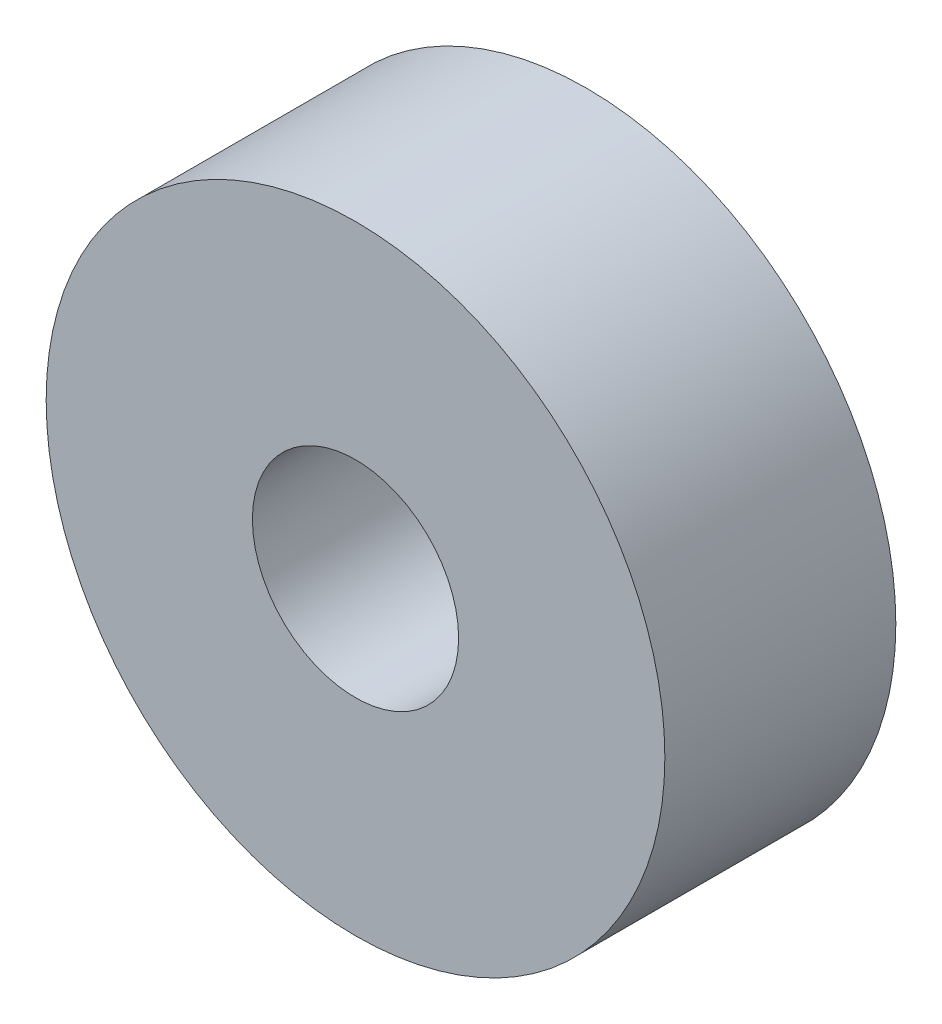
SolidWorks part; units mm, degrees
ref_plane "Front Plane" through (0, 0, 0) normal (0, 0, 1) x (1, 0, 0)
ref_plane "Top Plane" through (0, 0, 0) normal (0, 1, 0) x (1, 0, 0)
ref_plane "Right Plane" through (0, 0, 0) normal (1, 0, 0) x (0, 0, -1)
sketch "Sketch1" plane through (0, 0, 0) normal (0, 0, 1) x (1, 0, 0)
  circle A0 centre (0, 0) radius 3.175
  circle A1 centre (0, 0) radius 9.525
  dimension "D1" = 19.05
  dimension "D2" = 6.35
extrude "Boss-Extrude1" add sketch "Sketch1" along normal blind 7.112
